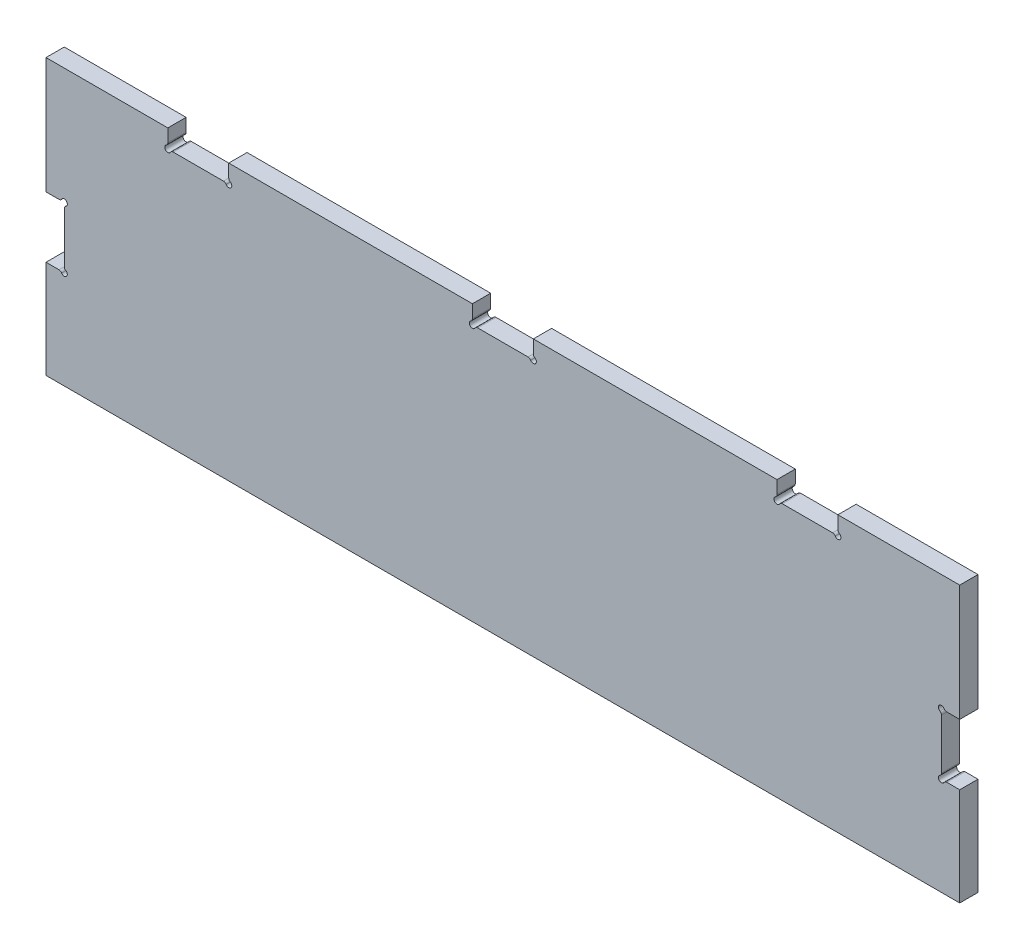
SolidWorks part; units mm, degrees
ref_plane "Front Plane" through (0, 0, 0) normal (0, 0, 1) x (1, 0, 0)
ref_plane "Top Plane" through (0, 0, 0) normal (0, 1, 0) x (1, 0, 0)
ref_plane "Right Plane" through (0, 0, 0) normal (1, 0, 0) x (0, 0, -1)
sketch "Sketch1" plane through (0, 0, 0) normal (0, 0, 1) x (1, 0, 0)
  line L0 (75, 3) -> (55, 3)
  line L1 (55, 0) -> (55, 3)
  line L2 (55, 0) -> (45, 0)
  line L3 (45, 0) -> (45, 3)
  line L4 (45, 3) -> (5, 3)
  line L5 (5, 0) -> (5, 3)
  line L6 (5, 0) -> (-5, 0)
  line L7 (-5, 0) -> (-5, 3)
  line L8 (-5, 3) -> (-45, 3)
  line L9 (-45, 0) -> (-45, 3)
  line L10 (-45, 0) -> (-55, 0)
  line L11 (-55, 0) -> (-55, 3)
  line L12 (-55, 3) -> (-75, 3)
  line L14 (-75, -42.2) -> (75, -42.2)
  line L22 (0, 0) -> (0, -42.2) construction
  line L30 (-75, -42.2) -> (-75, -21.1) construction
  line L31 (-75, -21.1) -> (-72, -21.1) construction
  line L32 (-72, -26.1) -> (-72, -16.1)
  line L33 (-72, -16.1) -> (-75, -16.1)
  line L34 (-72, -26.1) -> (-75, -26.1)
  line L35 (-75, 3) -> (-75, -16.1)
  line L36 (-75, -26.1) -> (-75, -42.2)
  line L37 (72, -26.1) -> (75, -26.1)
  line L38 (75, -26.1) -> (75, -42.2)
  line L39 (72, -26.1) -> (72, -16.1)
  line L40 (72, -16.1) -> (75, -16.1)
  line L41 (75, 3) -> (75, -16.1)
  point P14 (0, 0)
  point P23 (-72, -21.1)
  dimension "D1" = 45.2
  dimension "D2" = 21.1
  dimension "D3" = 3
  dimension "D4" = 10
  dimension "D5" = 20
  dimension "D6" = 10
  dimension "D7" = 3
  dimension "D8" = 40
  dimension "D9" = 10
  dimension "D10" = 150
  dimension "D11" = 40
  dimension "D12" = 10
  dimension "D13" = 20
  dimension "D14" = 3
  dimension "D15" = 3
  dimension "D16" = 3
  dimension "D17" = 3
  dimension "D18" = 3
extrude "Boss-Extrude1" add sketch "Sketch1" along normal mid plane 3
sketch "Sketch2" plane through (0, 0, 1.5) normal (0, 0, 1) x (1, 0, 0)
  circle A0 centre (-55, 0) radius 0.5
  circle A1 centre (-72, -16.1) radius 0.5
  circle A2 centre (-72, -26.1) radius 0.5
  circle A3 centre (-45, 0) radius 0.5
  circle A4 centre (-5, 0) radius 0.5
  circle A5 centre (5, 0) radius 0.5
  circle A6 centre (45, 0) radius 0.5
  circle A7 centre (55, 0) radius 0.5
  circle A8 centre (72, -16.1) radius 0.5
  circle A9 centre (72, -26.1) radius 0.5
  dimension "D1" = 1
  dimension "D2" = 1
  dimension "D3" = 1
  dimension "D4" = 1
  dimension "D5" = 1
  dimension "D6" = 1
  dimension "D7" = 1
  dimension "D8" = 1
  dimension "D9" = 1
  dimension "D10" = 1
extrude "Cut-Extrude1" cut sketch "Sketch2" against normal through all
fillet "Fillet1" radius 0.5 20 edges at (72.5, -16.1, 0) (72, -16.6, 0) (72.5, -26.1, 0) (72, -25.6, 0) (45, 0.5, 0) (45.5, 0, 0) (54.5, 0, 0) (55, 0.5, 0) (5, 0.5, 0) (4.5, 0, 0) (-5, 0.5, 0) (-4.5, 0, 0) (-72.5, -16.1, 0) (-72, -16.6, 0) (-72, -25.6, 0) (-72.5, -26.1, 0) (-54.5, 0, 0) (-55, 0.5, 0) (-45, 0.5, 0) (-45.5, 0, 0)
